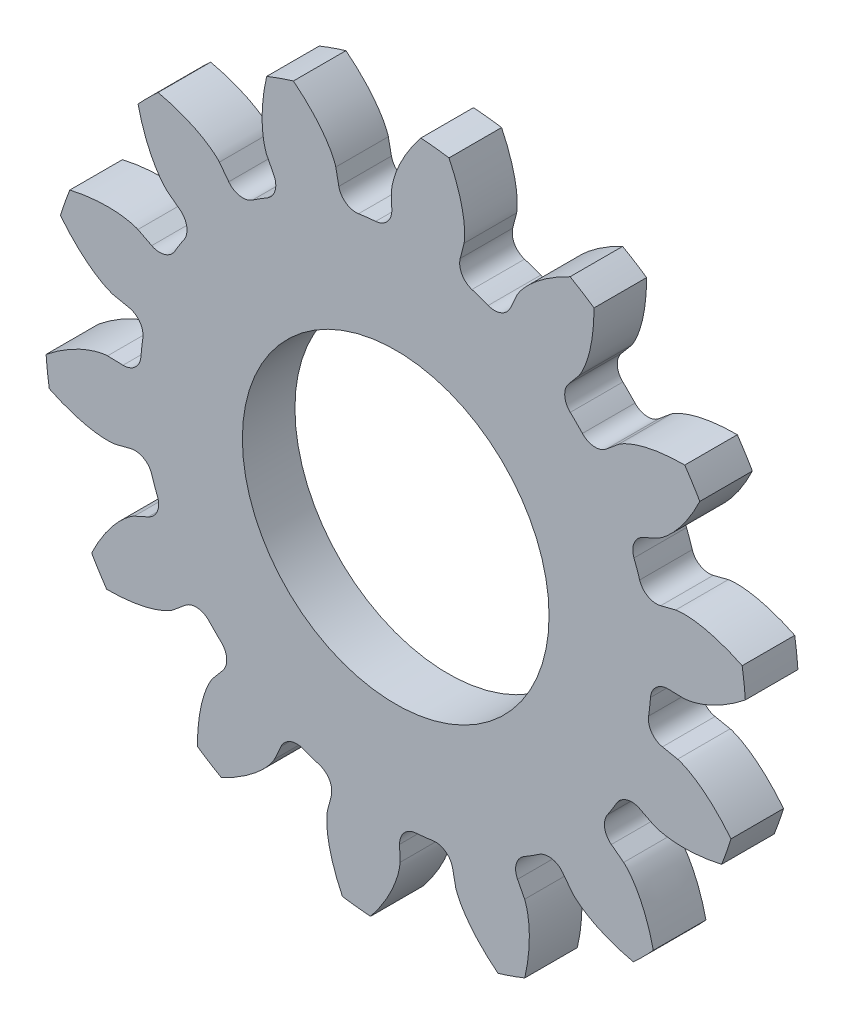
SolidWorks part; units mm, degrees
ref_plane "Front Plane" through (0, 0, 0) normal (0, 0, 1) x (1, 0, 0)
ref_plane "Top Plane" through (0, 0, 0) normal (0, 1, 0) x (1, 0, 0)
ref_plane "Right Plane" through (0, 0, 0) normal (1, 0, 0) x (0, 0, -1)
sketch "Sketch1" plane through (0, 0, 0) normal (0, 0, 1) x (1, 0, 0)
  line L0 (0, 0) -> (0, 110.697) construction
  line L1 (101.7811, 70) -> (-101.7811, 70) construction
  line L2 (-72.7092, 96.464) -> (72.7092, 43.536) construction
  line L3 (0, 0) -> (22.4976, 61.8116) construction
  line L4 (22.4976, 61.8116) -> (0, 70)
  line L5 (27.1265, 59.9246) -> (0.7607, 71.8598) construction
  line L6 (31.5989, 57.6916) -> (1.8302, 73.9965) construction
  line L7 (35.8887, 55.1254) -> (3.254, 76.3718) construction
  line L8 (39.9713, 52.2409) -> (5.0733, 78.9425) construction
  line L9 (17.7387, 63.3415) -> (-0.501, 68.4495) construction
  line L10 (12.8773, 64.5057) -> (-0.7943, 67.235) construction
  line L11 (7.9416, 65.2973) -> (-0.9344, 66.3768) construction
  line L12 (2.96, 65.7118) -> (-0.9774, 65.8892) construction
  line L13 (43.823, 49.0546) -> (7.3247, 81.6604) construction
  circle A0 centre (0, 0) radius 58.3333
  circle A1 centre (0, 0) radius 70 construction
  circle A2 centre (0, 0) radius 80 construction
  circle A3 centre (0, 0) radius 65.7785 construction
  arc A4 (22.4976, 61.8116) -> (17.7387, 63.3415) centre (0, 0) ccw
  arc A5 (17.7387, 63.3415) -> (12.8773, 64.5057) centre (0, 0) ccw
  arc A6 (12.8773, 64.5057) -> (7.9416, 65.2973) centre (0, 0) ccw
  arc A7 (22.4976, 61.8116) -> (27.1265, 59.9246) centre (0, 0) cw
  arc A8 (27.1265, 59.9246) -> (31.5989, 57.6916) centre (0, 0) cw
  arc A9 (31.5989, 57.6916) -> (35.8887, 55.1254) centre (0, 0) cw
  arc A10 (7.9416, 65.2973) -> (2.96, 65.7118) centre (0, 0) ccw
  arc A11 (35.8887, 55.1254) -> (39.9713, 52.2409) centre (0, 0) cw
  arc A12 (43.823, 49.0546) -> (39.9713, 52.2409) centre (0, 0) ccw
  point P10 (0, 70)
  point P11 (0, 70)
  dimension "D1" = 140
  dimension "D2" = 160
  dimension "D3" = 116.6667
  dimension "Base Diameter" = 131.557
  dimension "D4" = 20
  dimension "String Length" = 23.9414
  dimension "D5" = 28.9414
  dimension "D6" = 33.9414
  dimension "D7" = 38.9414
  dimension "D8" = 43.9414
  dimension "D9" = 18.9414
  dimension "D10" = 13.9414
  dimension "D11" = 8.9414
  dimension "D12" = 3.9414
  dimension "D13" = 48.9414
sketch "Sketch2" plane through (0, 0, 0) normal (0, 0, 1) x (1, 0, 0)
  line L0 (-0.9774, 65.7712) -> (-0.7979, 58.3279)
  line L1 (0, 0) -> (7.8375, 69.5599) construction
  line L2 (15.5884, 63.9047) -> (13.757, 56.6879)
  circle A0 centre (0, 0) radius 65.7785 construction
  circle A1 centre (0, 0) radius 80 construction
  circle A2 centre (0, 0) radius 80 construction
  circle A5 centre (0, 0) radius 58.3333 construction
  arc A6 (0, 70) -> (7.8375, 69.5599) centre (0, 0) cw
  arc A7 (5.7413, 79.7937) -> (12.1584, 79.0707) centre (0, 0) cw
  arc A8 (-0.7979, 58.3279) -> (13.757, 56.6879) centre (0, 0) cw
  spline S0 degree 3 poles (-0.9774, 65.7712) (-0.9783, 65.8106) (-0.9781, 66.0131) (-0.9232, 66.5036) (-0.7835, 67.3618) (-0.4831, 68.5763) (0.0219, 70.1269) (0.7881, 71.9867) (1.8627, 74.1232) (3.292, 76.4984) (4.6439, 78.4029) (5.5152, 79.5127) (5.7413, 79.7937) knots 0 0 0 0 0.006482 0.033375 0.081142 0.149784 0.2393 0.349691 0.480956 0.633096 0.806111 0.865537 0.865537 0.865537 0.865537
  spline S1 degree 3 poles (15.5884, 63.9047) (15.598, 63.9429) (15.6428, 64.1404) (15.6985, 64.6307) (15.7532, 65.4985) (15.7307, 66.7495) (15.5833, 68.3735) (15.2502, 70.3572) (14.6779, 72.6793) (13.813, 75.3129) (12.9188, 77.4705) (12.3163, 78.7464) (12.1584, 79.0707) knots 0 0 0 0 0.006482 0.033375 0.081142 0.149784 0.2393 0.349691 0.480956 0.633096 0.806111 0.865537 0.865537 0.865537 0.865537
  dimension "D1" = 7.854
extrude "Boss-Extrude1" add sketch "Sketch1" along normal blind 12 contours A0
extrude "Boss-Extrude2" add sketch "Sketch2" along normal up to surface (12 mm away) up to face at (58.3333, 0, 12)
fillet "Fillet1" radius 4 2 edges at (-0.7979, 58.3279, 6) (13.757, 56.6879, 6)
pattern_circular "CirPattern1" count 14 over 360 about axis through (0, 0, 12) along (0, 0, 1) of "Boss-Extrude2", "Fillet1"
sketch "Sketch3" plane through (0, 0, 12) normal (0, 0, 1) x (1, 0, 0)
  circle A0 centre (0, 0) radius 35
  dimension "D1" = 70
extrude "Cut-Extrude1" cut sketch "Sketch3" against normal through all
equation "\"m\"= 10'Module"
equation "\"Z\"= 14'Number of Teeth"
equation "\"a\"= 20deg'Pressure Angle"
equation "\"Dp\"= \"m\" * \"Z\"'Pitch Diameter"
equation "\"De\"= \"Dp\" + 2 * \"m\""
equation "\"Di\"= \"Dp\" - 2 * 7 / 6 * \"m\""
equation "\"r\"= 0.4 * \"m\""
equation "\"D1@Sketch1\"= \"Dp\""
equation "\"D2@Sketch1\"= \"De\""
equation "\"D3@Sketch1\"= \"Di\""
equation "\"D4@Sketch1\"= \"a\""
equation "\"D5@Sketch1\"= \"String Length@Sketch1\" + 1 * \"Arc Length@Sketch1\""
equation "\"D6@Sketch1\"= \"String Length@Sketch1\" + 2 * \"Arc Length@Sketch1\""
equation "\"D7@Sketch1\"= \"String Length@Sketch1\" + 3 * \"Arc Length@Sketch1\""
equation "\"D8@Sketch1\"= \"String Length@Sketch1\" + 4 * \"Arc Length@Sketch1\""
equation "\"D9@Sketch1\"= \"String Length@Sketch1\" - 1 * \"Arc Length@Sketch1\""
equation "\"D10@Sketch1\"= \"String Length@Sketch1\" - 2 * \"Arc Length@Sketch1\""
equation "\"D11@Sketch1\"= \"String Length@Sketch1\" - 3 * \"Arc Length@Sketch1\""
equation "\"D12@Sketch1\"= \"String Length@Sketch1\" - 4 * \"Arc Length@Sketch1\""
equation "\"D13@Sketch1\"= \"String Length@Sketch1\" + 5 * \"Arc Length@Sketch1\""
equation "\"P\"= Pi * \"m\"'Pitch"
equation "\"D1@Sketch2\" = \"P\" / 4"
